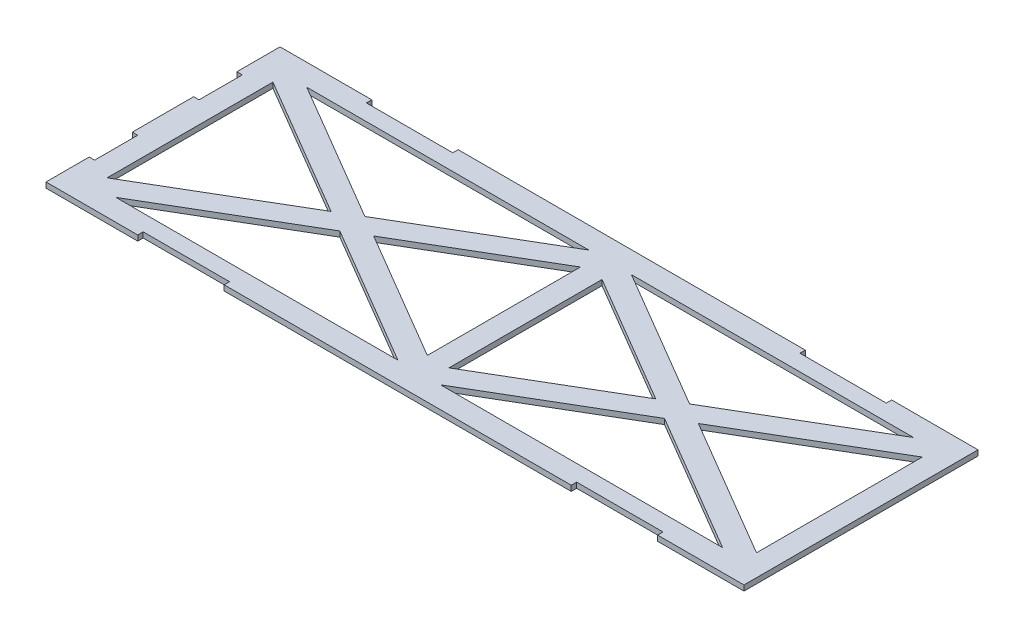
SolidWorks part; units mm, degrees
ref_plane "Front Plane" through (0, 0, 0) normal (0, 0, 1) x (1, 0, 0)
ref_plane "Top Plane" through (0, 0, 0) normal (0, 1, 0) x (1, 0, 0)
ref_plane "Right Plane" through (0, 0, 0) normal (1, 0, 0) x (0, 0, -1)
sketch "Sketch1" plane through (0, 0, 0) normal (0, 1, 0) x (1, 0, 0)
  line L0 (-200.5203, 68.834) -> (-200.5203, -68.834) construction
  line L1 (-203.6953, 68.834) -> (-152.8953, 68.834)
  line L2 (-206.8703, 18.034) -> (-206.8703, -18.034)
  line L3 (-203.6953, -68.834) -> (-152.8953, -68.834)
  line L4 (203.6953, 68.834) -> (203.6953, -68.834)
  line L5 (-203.6953, 65.659) -> (203.6953, 65.659) construction
  line L6 (-203.6953, -65.659) -> (203.6953, -65.659) construction
  line L7 (-203.6953, 18.034) -> (-206.8703, 18.034)
  line L8 (-203.6953, 43.434) -> (-203.6953, 18.034)
  line L9 (-203.6953, 43.434) -> (-203.6953, 18.034)
  line L10 (-203.6953, -18.034) -> (-203.6953, -43.434)
  line L11 (-203.6953, -18.034) -> (-203.6953, -43.434)
  line L12 (-206.8703, -43.434) -> (-206.8703, -68.834)
  line L13 (-152.8953, 68.834) -> (-152.8953, 65.659)
  line L14 (-152.8953, 65.659) -> (-102.0953, 65.659)
  line L15 (-102.0953, 65.659) -> (-102.0953, 68.834)
  line L16 (-152.8953, -68.834) -> (-152.8953, -65.659)
  line L17 (-152.8953, -65.659) -> (-102.0953, -65.659)
  line L18 (-102.0953, -65.659) -> (-102.0953, -68.834)
  line L19 (102.0953, 65.659) -> (102.0953, 68.834)
  line L20 (102.0953, 65.659) -> (152.8953, 65.659)
  line L21 (152.8953, 65.659) -> (152.8953, 68.834)
  line L22 (102.0953, -68.834) -> (102.0953, -65.659)
  line L23 (102.0953, -65.659) -> (152.8953, -65.659)
  line L24 (152.8953, -65.659) -> (152.8953, -68.834)
  line L25 (0, 68.834) -> (0, -68.834) construction
  line L26 (-178.4643, 56.134) -> (-12.531, 56.134)
  line L27 (-190.9953, 48.7682) -> (-190.9953, -48.7682)
  line L28 (-178.4643, -56.134) -> (-12.531, -56.134)
  line L29 (190.9953, 48.7682) -> (190.9953, -48.7682)
  line L30 (-190.9953, 56.134) -> (0, -56.134) construction
  line L31 (0, 56.134) -> (-190.9953, -56.134) construction
  line L32 (0, 56.134) -> (190.9953, -56.134) construction
  line L33 (190.9953, 56.134) -> (0, -56.134) construction
  line L34 (-95.4976, 7.3658) -> (-12.531, 56.134)
  line L35 (6.35, 45.0357) -> (6.35, -45.0357)
  line L36 (-190.9953, 48.7682) -> (-108.0286, 0)
  line L37 (-178.4643, 56.134) -> (-95.4976, 7.3658)
  line L38 (-190.9953, -48.7682) -> (-108.0286, 0)
  line L39 (-178.4643, -56.134) -> (-95.4976, -7.3658)
  line L40 (6.35, 45.0357) -> (82.9667, 0)
  line L41 (12.531, 56.134) -> (95.4977, 7.3658)
  line L42 (6.35, -45.0357) -> (82.9667, 0)
  line L43 (190.9953, 48.7682) -> (108.0286, 0)
  line L44 (-203.6953, 43.434) -> (-206.8703, 43.434)
  line L45 (-203.6953, 68.834) -> (-206.8703, 68.834)
  line L46 (-102.0953, 68.834) -> (102.0953, 68.834)
  line L47 (-203.6953, -68.834) -> (-206.8703, -68.834)
  line L48 (-206.8703, 68.834) -> (-206.8703, 43.434)
  line L49 (-203.6953, 43.434) -> (-203.6953, 18.034)
  line L50 (-206.8703, -18.034) -> (-203.6953, -18.034)
  line L51 (-203.6953, -43.434) -> (-206.8703, -43.434)
  line L52 (12.531, 56.134) -> (178.4643, 56.134)
  line L53 (-6.35, 45.0357) -> (-6.35, -45.0357)
  line L54 (12.531, -56.134) -> (178.4643, -56.134)
  line L55 (-95.4976, -7.3658) -> (-12.531, -56.134)
  line L56 (-82.9667, 0) -> (-6.35, -45.0357)
  line L57 (-82.9667, 0) -> (-6.35, 45.0357)
  line L58 (95.4977, 7.3658) -> (178.4643, 56.134)
  line L59 (95.4977, -7.3658) -> (178.4643, -56.134)
  line L60 (95.4977, -7.3658) -> (12.531, -56.134)
  line L61 (108.0286, 0) -> (190.9953, -48.7682)
  line L62 (152.8953, 68.834) -> (203.6953, 68.834)
  line L63 (152.8953, -68.834) -> (203.6953, -68.834)
  line L64 (-102.0953, -68.834) -> (102.0953, -68.834)
  point P6 (203.6953, 0)
  dimension "D1" = 137.668
  dimension "D2" = 407.3906
  dimension "D3" = 3.175
  dimension "D4" = 3.175
  dimension "D11" = 50.8
  dimension "D12" = 50.8
  dimension "D13" = 50.8
  dimension "D14" = 50.8
  dimension "D15" = 50.8
  dimension "D16" = 50.8
  dimension "D18" = 12.7
  dimension "D19" = 12.7
  dimension "D22" = 6.35
  dimension "D23" = 6.35
  dimension "D24" = 6.35
  dimension "D25" = 6.35
  dimension "D26" = 6.35
  dimension "D27" = 6.35
  dimension "D28" = 6.35
  dimension "D29" = 6.35
extrude "Boss-Extrude1" add sketch "Sketch1" along normal blind 3.175 contours L18 L64 L22 L23 L24 L63 L4 L62 L21 L20 L19 L46 L15 L14 L13 L1 L45 L48 L44 L8 L7 L2 L50 L10 L51 L12 L47 L3 L16 L17 L56 L57 L53 L39 L55 L28 L37 L26 L34 L38 L27 L36 L42 L35 L40
